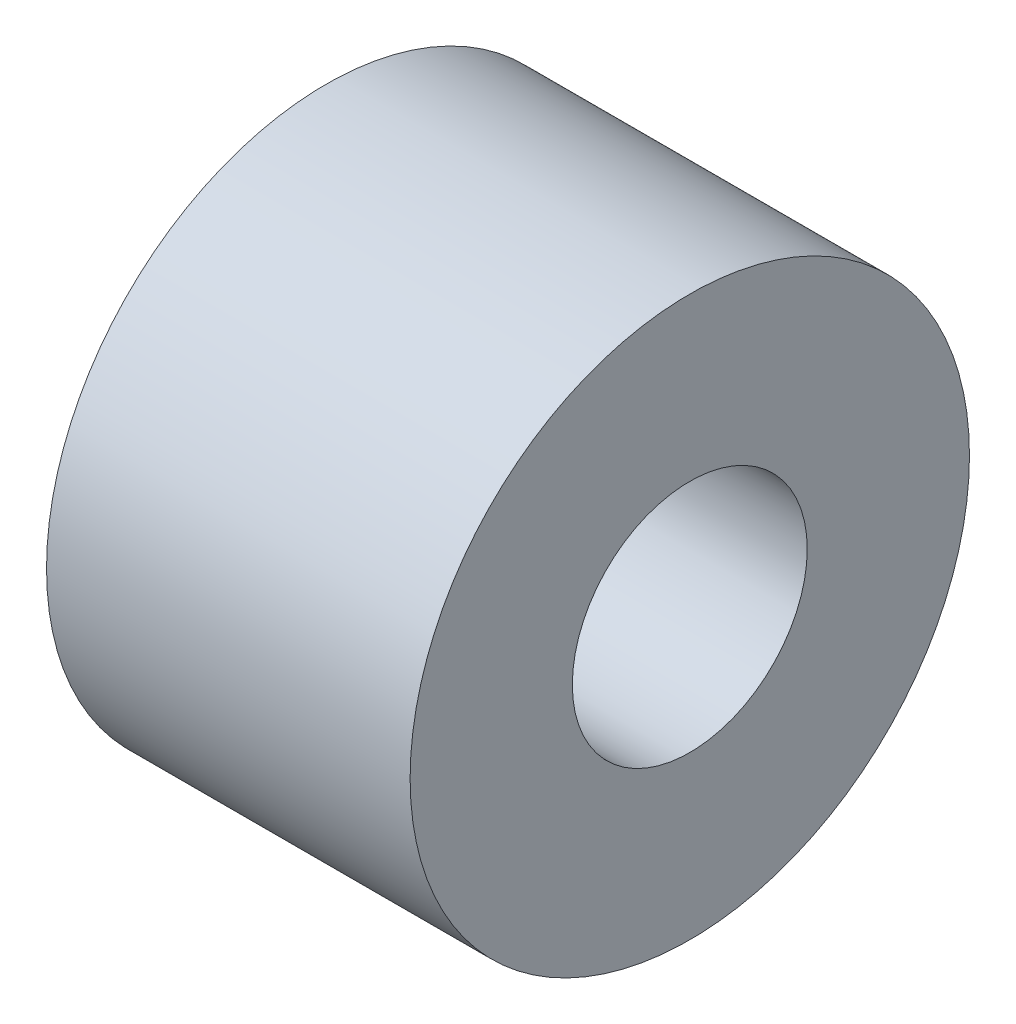
SolidWorks part; units mm, degrees
ref_plane "Front Plane" through (0, 0, 0) normal (0, 0, 1) x (1, 0, 0)
ref_plane "Top Plane" through (0, 0, 0) normal (0, 1, 0) x (1, 0, 0)
ref_plane "Right Plane" through (0, 0, 0) normal (1, 0, 0) x (0, 0, -1)
sketch "Sketch1" plane through (0, 0, 0) normal (1, 0, 0) x (0, 0, -1)
  circle A0 centre (0, 0) radius 10
  circle A1 centre (0, 0) radius 4.2
  point P5 (1.1782, 0)
  dimension "D1" = 20
  dimension "D2" = 8.4
extrude "Boss-Extrude1" add sketch "Sketch1" along normal blind 13
